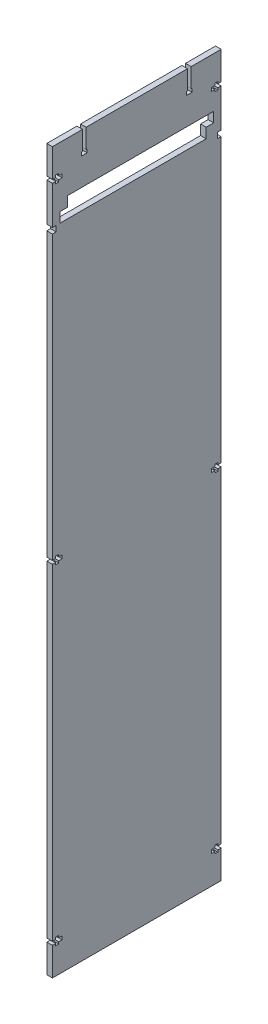
SolidWorks part; units mm, degrees
ref_plane "Front Plane" through (0, 0, 0) normal (0, 0, 1) x (1, 0, 0)
ref_plane "Top Plane" through (0, 0, 0) normal (0, 1, 0) x (1, 0, 0)
ref_plane "Right Plane" through (0, 0, 0) normal (1, 0, 0) x (0, 0, -1)
sketch "Sketch1" plane through (0, 0, 0) normal (0, 1, 0) x (1, 0, 0)
  line L1 (0, 0) -> (4.7625, 0)
  line L2 (0, 0) -> (0, 142.875)
  line L3 (0, 142.875) -> (4.7625, 142.875)
  line L4 (4.7625, 0) -> (4.7625, 142.875)
  dimension "D1" = 142.875
  dimension "D2" = 4.7625
extrude "Boss-Extrude1" add sketch "Sketch1" along normal blind 609.6
sketch "Sketch12" plane through (0, 0, 0) normal (-1, 0, 0) x (0, 0, 1)
  line L0 (0, 609.6) -> (0, 0) construction
  line L1 (-6.35, 550.291) -> (-130.175, 550.291)
  line L2 (-6.35, 550.291) -> (-6.35, 558.8)
  line L3 (-6.35, 558.8) -> (-130.175, 558.8)
  line L4 (-130.175, 550.291) -> (-130.175, 558.8)
  line L5 (-142.875, 609.6) -> (0, 609.6) construction
  dimension "D1" = 123.825
  dimension "D2" = 6.35
  dimension "D3" = 50.8
  dimension "D4" = 8.509
extrude "Cut-Extrude7" cut sketch "Sketch12" against normal through all
sketch "Sketch13" plane through (0, 0, 0) normal (-1, 0, 0) x (0, 0, 1)
  line L0 (-6.35, 558.8) -> (-130.175, 558.8) construction
  line L1 (-12.7, 558.8) -> (-136.525, 558.8)
  line L2 (-12.7, 558.8) -> (-12.7, 567.309)
  line L3 (-12.7, 567.309) -> (-136.525, 567.309)
  line L4 (-136.525, 558.8) -> (-136.525, 567.309)
  line L5 (-142.875, 609.6) -> (-142.875, 0) construction
  point P6 (-136.525, 563.0545)
  dimension "D1" = 123.825
  dimension "D2" = 8.509
  dimension "D3" = 6.35
extrude "Cut-Extrude8" cut sketch "Sketch13" against normal through all
sketch "Sketch14" plane through (0, 0, 0) normal (-1, 0, 0) x (0, 0, 1)
  line L0 (-6.35, 550.291) -> (-6.35, 558.8) construction
  line L1 (-12.7, 558.8) -> (-12.7, 567.309) construction
  line L2 (-6.35, 558.8) -> (-12.7, 558.8) construction
  line L3 (-130.175, 550.291) -> (-6.35, 550.291) construction
  line L4 (-130.175, 558.8) -> (-130.175, 550.291) construction
  line L5 (-136.525, 558.8) -> (-130.175, 558.8) construction
  line L6 (-136.525, 567.309) -> (-136.525, 558.8) construction
  line L7 (-12.7, 567.309) -> (-136.525, 567.309) construction
  line L8 (-6.35, 550.291) -> (-6.35, 558.8)
  line L9 (-12.7, 558.8) -> (-12.7, 567.309)
  line L10 (-6.35, 558.8) -> (-12.7, 558.8)
  line L11 (-130.175, 550.291) -> (-6.35, 550.291)
  line L12 (-130.175, 558.8) -> (-130.175, 550.291)
  line L13 (-136.525, 558.8) -> (-130.175, 558.8)
  line L14 (-136.525, 567.309) -> (-136.525, 558.8)
  line L15 (-12.7, 567.309) -> (-136.525, 567.309)
  line L16 (-130.302, 550.164) -> (-6.223, 550.164)
  line L17 (-6.223, 550.164) -> (-6.223, 558.927)
  line L18 (-6.223, 558.927) -> (-12.573, 558.927)
  line L19 (-12.573, 558.927) -> (-12.573, 567.436)
  line L20 (-12.573, 567.436) -> (-136.652, 567.436)
  line L21 (-136.652, 567.436) -> (-136.652, 558.673)
  line L22 (-136.652, 558.673) -> (-130.302, 558.673)
  line L23 (-130.302, 558.673) -> (-130.302, 550.164)
  dimension "D1" = 0.127
extrude "Cut-Extrude9" [suppressed] cut sketch "Sketch14" against normal through all
sketch "Sketch15" plane through (0, 0, 0) normal (-1, 0, 0) x (0, 0, 1)
  line L0 (0, 550.291) -> (-142.875, 550.291) construction
  line L1 (0, 609.6) -> (0, 0) construction
  line L2 (-142.875, 609.6) -> (-142.875, 0) construction
  line L4 (0, 550.291) -> (-3.175, 550.291)
  line L5 (0, 550.291) -> (0, 545.5285)
  line L6 (0, 545.5285) -> (-3.175, 545.5285)
  line L7 (-3.175, 550.291) -> (-3.175, 545.5285)
  line L8 (-142.875, 550.291) -> (-139.7, 550.291)
  line L9 (-142.875, 550.291) -> (-142.875, 545.5285)
  line L10 (-142.875, 545.5285) -> (-139.7, 545.5285)
  line L11 (-139.7, 550.291) -> (-139.7, 545.5285)
  dimension "D1" = 3.175
  dimension "D2" = 4.7625
extrude "Cut-Extrude10" cut sketch "Sketch15" against normal through all
sketch "Sketch16" plane through (0, 0, 0) normal (-1, 0, 0) x (0, 0, 1)
  line L0 (0, 25.4) -> (-142.875, 25.4) construction
  line L1 (0, 545.5285) -> (0, 0) construction
  line L2 (-142.875, 545.5285) -> (-142.875, 0) construction
  line L3 (-71.4375, 0) -> (-71.4375, 609.6) construction
  line L4 (-142.875, 0) -> (0, 0) construction
  line L5 (-142.875, 609.6) -> (0, 609.6) construction
  line L6 (-2.794, 23.9395) -> (-2.794, 22.1996)
  line L7 (-8.128, 23.9395) -> (-5.334, 23.9395)
  line L8 (-8.128, 23.9395) -> (-8.128, 26.8605)
  line L9 (-8.128, 26.8605) -> (-5.334, 26.8605)
  line L10 (0, 23.9395) -> (0, 26.8605)
  line L11 (-8.128, 23.9395) -> (0, 26.8605) construction
  line L12 (-8.128, 26.8605) -> (0, 23.9395) construction
  line L13 (-2.794, 28.6004) -> (-5.334, 28.6004)
  line L14 (-2.794, 28.6004) -> (-2.794, 26.8605)
  line L15 (-2.794, 22.1996) -> (-5.334, 22.1996)
  line L16 (-5.334, 28.6004) -> (-5.334, 26.8605)
  line L17 (-2.794, 28.6004) -> (-5.334, 22.1996) construction
  line L18 (-2.794, 22.1996) -> (-5.334, 28.6004) construction
  line L19 (-2.794, 23.9395) -> (0, 23.9395)
  line L20 (-5.334, 23.9395) -> (-5.334, 22.1996)
  line L21 (-2.794, 26.8605) -> (0, 26.8605)
  line L22 (-134.747, 26.8605) -> (-137.541, 26.8605)
  line L23 (-134.747, 23.9395) -> (-134.747, 26.8605)
  line L24 (-134.747, 23.9395) -> (-137.541, 23.9395)
  line L25 (-137.541, 23.9395) -> (-137.541, 22.1996)
  line L26 (-140.081, 22.1996) -> (-137.541, 22.1996)
  line L27 (-140.081, 23.9395) -> (-140.081, 22.1996)
  line L28 (-140.081, 23.9395) -> (-142.875, 23.9395)
  line L29 (-142.875, 23.9395) -> (-142.875, 26.8605)
  line L30 (-140.081, 26.8605) -> (-142.875, 26.8605)
  line L31 (-140.081, 28.6004) -> (-140.081, 26.8605)
  line L32 (-140.081, 28.6004) -> (-137.541, 28.6004)
  line L33 (-137.541, 28.6004) -> (-137.541, 26.8605)
  line L34 (-134.747, 306.2605) -> (-137.541, 306.2605)
  line L35 (-134.747, 303.3395) -> (-134.747, 306.2605)
  line L36 (-134.747, 303.3395) -> (-137.541, 303.3395)
  line L37 (-137.541, 303.3395) -> (-137.541, 301.5996)
  line L38 (-140.081, 301.5996) -> (-137.541, 301.5996)
  line L39 (-140.081, 303.3395) -> (-140.081, 301.5996)
  line L40 (-140.081, 303.3395) -> (-142.875, 303.3395)
  line L41 (-142.875, 303.3395) -> (-142.875, 306.2605)
  line L42 (-140.081, 306.2605) -> (-142.875, 306.2605)
  line L43 (-140.081, 308.0004) -> (-140.081, 306.2605)
  line L44 (-140.081, 308.0004) -> (-137.541, 308.0004)
  line L45 (-137.541, 308.0004) -> (-137.541, 306.2605)
  line L46 (-2.794, 303.3395) -> (-2.794, 301.5996)
  line L47 (-8.128, 303.3395) -> (-5.334, 303.3395)
  line L48 (-8.128, 303.3395) -> (-8.128, 306.2605)
  line L49 (-8.128, 306.2605) -> (-5.334, 306.2605)
  line L50 (0, 303.3395) -> (0, 306.2605)
  line L51 (-2.794, 308.0004) -> (-5.334, 308.0004)
  line L52 (-2.794, 308.0004) -> (-2.794, 306.2605)
  line L53 (-2.794, 301.5996) -> (-5.334, 301.5996)
  line L54 (-5.334, 308.0004) -> (-5.334, 306.2605)
  line L55 (-2.794, 303.3395) -> (0, 303.3395)
  line L56 (-5.334, 303.3395) -> (-5.334, 301.5996)
  line L57 (-2.794, 306.2605) -> (0, 306.2605)
  line L58 (0, 304.8) -> (-142.875, 304.8) construction
  line L59 (-8.128, 303.3395) -> (0, 306.2605) construction
  line L60 (-8.128, 306.2605) -> (0, 303.3395) construction
  line L61 (-2.794, 308.0004) -> (-5.334, 301.5996) construction
  line L62 (-2.794, 301.5996) -> (-5.334, 308.0004) construction
  line L63 (-134.747, 585.6605) -> (-137.541, 585.6605)
  line L64 (-134.747, 582.7395) -> (-134.747, 585.6605)
  line L65 (-134.747, 582.7395) -> (-137.541, 582.7395)
  line L66 (-137.541, 582.7395) -> (-137.541, 580.9996)
  line L67 (-140.081, 580.9996) -> (-137.541, 580.9996)
  line L68 (-140.081, 582.7395) -> (-140.081, 580.9996)
  line L69 (-140.081, 582.7395) -> (-142.875, 582.7395)
  line L70 (-142.875, 582.7395) -> (-142.875, 585.6605)
  line L71 (-140.081, 585.6605) -> (-142.875, 585.6605)
  line L72 (-140.081, 587.4004) -> (-140.081, 585.6605)
  line L73 (-140.081, 587.4004) -> (-137.541, 587.4004)
  line L74 (-137.541, 587.4004) -> (-137.541, 585.6605)
  line L75 (-2.794, 582.7395) -> (-2.794, 580.9996)
  line L76 (-8.128, 582.7395) -> (-5.334, 582.7395)
  line L77 (-8.128, 582.7395) -> (-8.128, 585.6605)
  line L78 (-8.128, 585.6605) -> (-5.334, 585.6605)
  line L79 (0, 582.7395) -> (0, 585.6605)
  line L80 (-2.794, 587.4004) -> (-5.334, 587.4004)
  line L81 (-2.794, 587.4004) -> (-2.794, 585.6605)
  line L82 (-2.794, 580.9996) -> (-5.334, 580.9996)
  line L83 (-5.334, 587.4004) -> (-5.334, 585.6605)
  line L84 (-2.794, 582.7395) -> (0, 582.7395)
  line L85 (-5.334, 582.7395) -> (-5.334, 580.9996)
  line L86 (-2.794, 585.6605) -> (0, 585.6605)
  line L87 (0, 584.2) -> (-142.875, 584.2) construction
  line L88 (-8.128, 582.7395) -> (0, 585.6605) construction
  line L89 (-8.128, 585.6605) -> (0, 582.7395) construction
  line L90 (-2.794, 587.4004) -> (-5.334, 580.9996) construction
  line L91 (-2.794, 580.9996) -> (-5.334, 587.4004) construction
  point P12 (-4.064, 25.4)
  point P17 (-4.064, 25.4)
  point P42 (-4.064, 304.8)
  point P47 (-4.064, 304.8)
  point P70 (-4.064, 584.2)
  point P75 (-4.064, 584.2)
  dimension "D1" = 8.128
  dimension "D2" = 2.921
  dimension "D3" = 25.4
  dimension "D4" = 2.54
  dimension "D5" = 6.4008
  dimension "D6" = 3
extrude "Cut-Extrude11" cut sketch "Sketch16" against normal through all
sketch "Sketch17" plane through (0, 0, 0) normal (-1, 0, 0) x (0, 0, 1)
  line L1 (-71.4375, 609.6) -> (-71.4375, 567.309) construction
  line L4 (-142.875, 609.6) -> (0, 609.6) construction
  line L5 (-12.7, 567.309) -> (-136.525, 567.309) construction
  line L6 (-26.9875, 609.6) -> (-115.8875, 609.6) construction
  line L7 (-26.9875, 609.6) -> (-26.9875, 590.9829) construction
  line L8 (-28.5115, 593.3374) -> (-29.3497, 593.3374)
  line L9 (-117.4115, 609.6) -> (-114.3635, 609.6)
  line L10 (-25.4635, 593.3374) -> (-25.4635, 609.6)
  line L11 (-25.4635, 609.6) -> (-28.5115, 609.6)
  line L12 (-28.5115, 593.3374) -> (-28.5115, 609.6)
  line L13 (-25.5092, 593.3374) -> (-28.5115, 609.6) construction
  line L14 (-25.4635, 609.6) -> (-28.4658, 593.3374) construction
  line L15 (-24.6253, 590.4164) -> (-29.3497, 590.4164)
  line L16 (-24.6253, 590.4164) -> (-24.6253, 593.3374)
  line L17 (-24.6253, 593.3374) -> (-25.4635, 593.3374)
  line L18 (-29.3497, 590.4164) -> (-29.3497, 593.3374)
  line L19 (-24.6253, 590.4164) -> (-29.3497, 593.3374) construction
  line L20 (-24.6253, 593.3374) -> (-29.3497, 590.4164) construction
  line L21 (-114.3635, 593.3374) -> (-114.3635, 609.6)
  line L22 (-117.4115, 593.3374) -> (-117.4115, 609.6)
  line L23 (-118.2497, 590.4164) -> (-118.2497, 593.3374)
  line L24 (-114.3635, 593.3374) -> (-113.5253, 593.3374)
  line L25 (-113.5253, 590.4164) -> (-113.5253, 593.3374)
  line L26 (-118.2497, 590.4164) -> (-113.5253, 590.4164)
  line L27 (-117.4115, 593.3374) -> (-118.2497, 593.3374)
  point P8 (-71.4375, 609.6)
  point P10 (-26.9875, 601.345)
  point P15 (-26.9875, 591.8769)
  dimension "D1" = 88.9
  dimension "D4" = 4.7244
  dimension "D5" = 2.921
extrude "Cut-Extrude12" cut sketch "Sketch17" against normal through all
